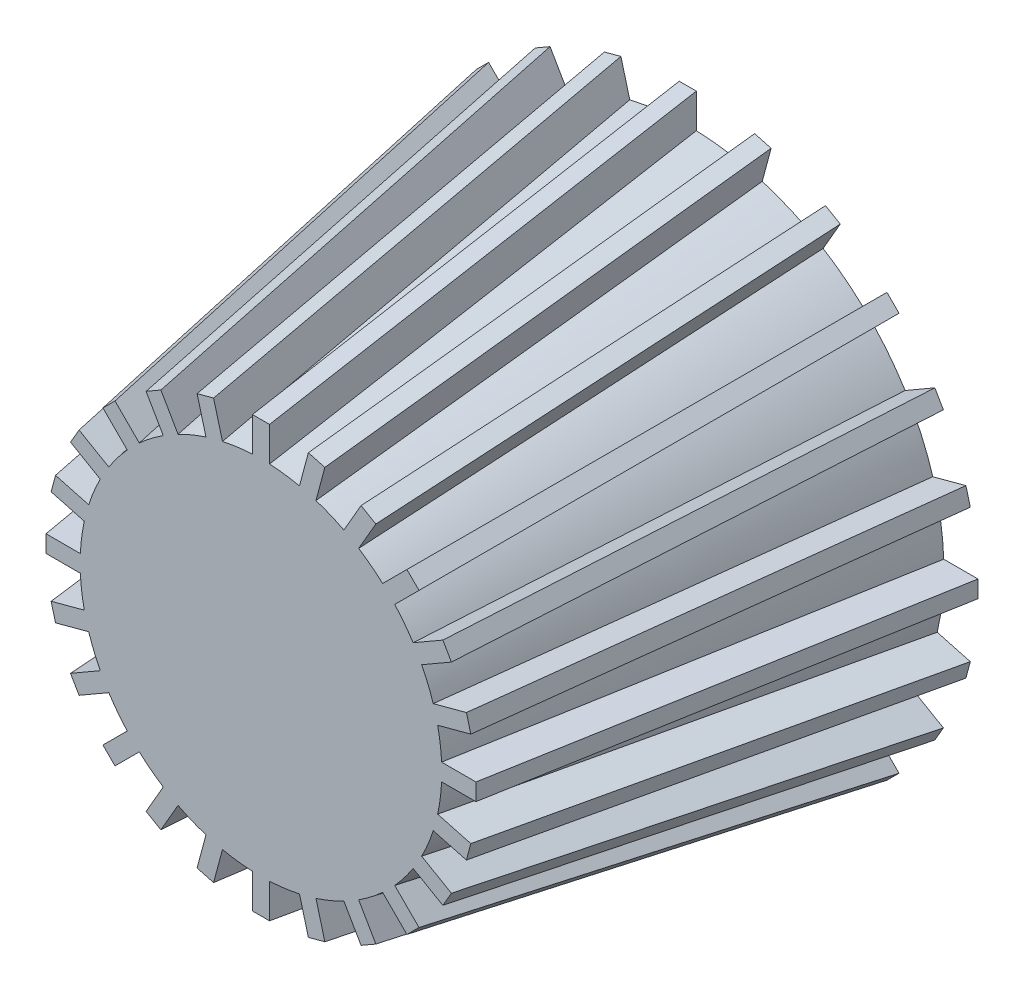
SolidWorks part; units mm, degrees
ref_plane "Front Plane" through (0, 0, 0) normal (0, 0, 1) x (1, 0, 0)
ref_plane "Top Plane" through (0, 0, 0) normal (0, 1, 0) x (1, 0, 0)
ref_plane "Right Plane" through (0, 0, 0) normal (1, 0, 0) x (0, 0, -1)
sketch "Sketch1" plane through (0, 0, 0) normal (0, 0, 1) x (1, 0, 0)
  circle A1 centre (0, 0) radius 30
  dimension "D2" = 60
extrude "Boss-Extrude6" add sketch "Sketch1" along normal blind 50 draft 10 contours A1
sketch "Sketch5" plane through (0, 0, 0) normal (0, 0, 1) x (1, 0, 0)
  circle A0 centre (0, 0) radius 28
  dimension "D1" = 56
extrude "Cut-Extrude1" cut sketch "Sketch5" along normal blind 50 draft 10
sketch "Sketch6" plane through (0, 0, 50) normal (0, 0, 1) x (1, 0, 0)
  circle A0 centre (0, 0) radius 21.1837 construction
  circle A1 centre (0, 0) radius 21.1837
extrude "Boss-Extrude7" add sketch "Sketch6" against normal blind 5
sketch "Sketch7" plane through (0, 0, 0) normal (1, 0, 0) x (0, 0, -1)
  line L0 (0, 28) -> (-50, 19.1837)
  line L1 (-50, 21.1837) -> (-50, -21.1837) construction
  line L2 (-50, 19.1837) -> (-50, 25.1837)
  line L3 (-50, 25.1837) -> (0, 34)
  line L4 (0, 34) -> (0, 28)
  line L5 (0, -30) -> (0, 30) construction
  dimension "D1" = 6
  dimension "D2" = 80
extrude "Boss-Extrude8" add sketch "Sketch7" along normal mid plane 2
pattern_circular "CirPattern2" count 24 over 360 about axis through (0, 0, 0) along (0, 0, 1) of "Boss-Extrude8"
